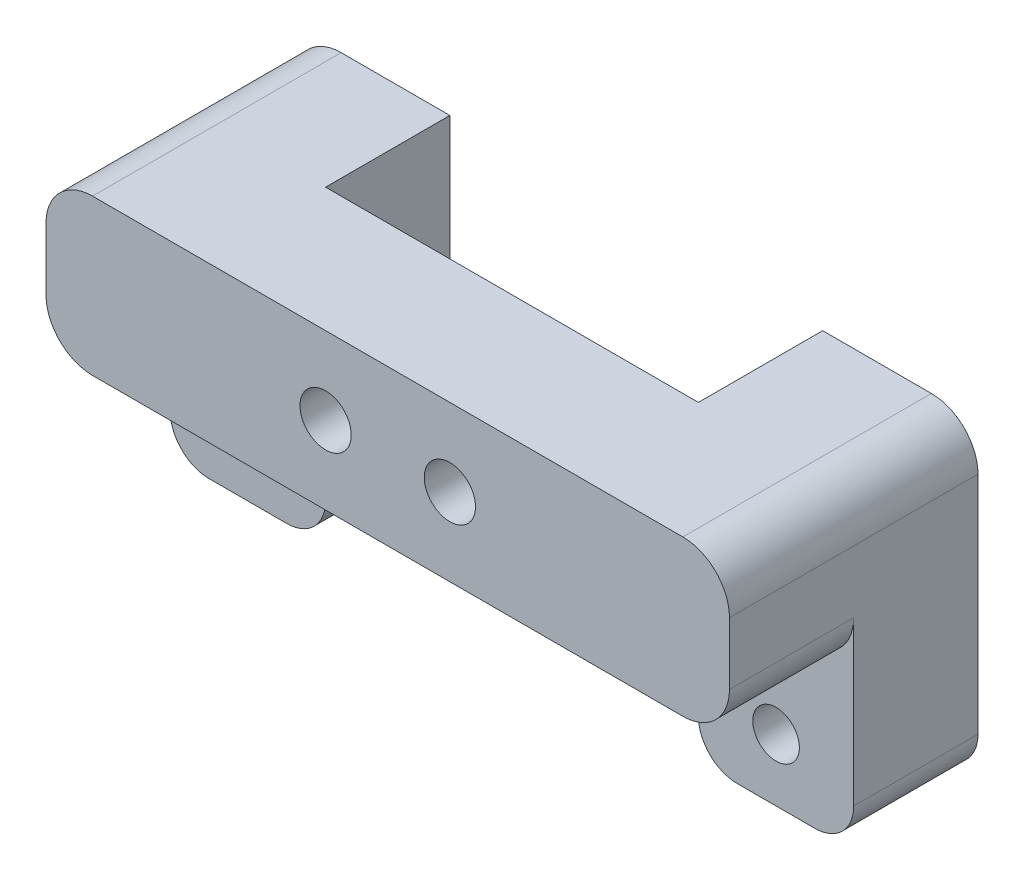
SolidWorks part; units mm, degrees
ref_plane "Front" through (0, 0, 0) normal (0, 0, 1) x (1, 0, 0)
ref_plane "Top" through (0, 0, 0) normal (0, 1, 0) x (1, 0, 0)
ref_plane "Right" through (0, 0, 0) normal (1, 0, 0) x (0, 0, -1)
sketch "Sketch1" plane through (0, 0, 0) normal (0, 0, 1) x (1, 0, 0)
  line L1 (0, 0) -> (44, 0)
  line L2 (0, 0) -> (0, -10)
  line L3 (0, -10) -> (44, -10)
  line L4 (44, 0) -> (44, -10)
  dimension "D1" = 10
  dimension "D2" = 44
extrude "Boss-Extrude1" add sketch "Sketch1" along normal blind 8
sketch "Sketch4" plane through (0, 0, 0) normal (0, 0, -1) x (-1, 0, 0)
  line L0 (-44, 0) -> (0, 0) construction
  line L1 (0, -10) -> (-10, -10)
  line L2 (0, -10) -> (0, 0)
  line L3 (0, 0) -> (-10, 0)
  line L4 (-10, -10) -> (-10, 0)
  line L6 (-44, -10) -> (-34, -10)
  line L7 (-44, -10) -> (-44, 0)
  line L8 (-44, 0) -> (-34, 0)
  line L9 (-34, -10) -> (-34, 0)
  dimension "D1" = 10
  dimension "D2" = 10
extrude "Boss-Extrude2" add sketch "Sketch4" along normal blind 8
sketch "Sketch3" plane through (0, 0, 8) normal (0, 0, 1) x (1, 0, 0)
  line L0 (0, -10) -> (44, -10) construction
  line L1 (0, 0) -> (0, -10) construction
  line L2 (44, -10) -> (44, 0) construction
  circle A0 centre (18, -5) radius 1.65
  circle A1 centre (26, -5) radius 1.65
  dimension "D1" = 3.3
  dimension "D2" = 3.3
  dimension "D3" = 5
  dimension "D4" = 5
  dimension "D5" = 18
  dimension "D6" = 18
extrude "Cut-Extrude2" cut sketch "Sketch3" against normal through all
sketch "Sketch5" plane through (0, -10, 0) normal (0, -1, 0) x (-1, 0, 0)
  line L1 (-10, 0) -> (0, 0)
  line L2 (-10, 0) -> (-10, 8)
  line L3 (-10, 8) -> (0, 8)
  line L4 (0, 0) -> (0, 8)
  line L5 (-34, 0) -> (-44, 0)
  line L6 (-34, 0) -> (-34, 8)
  line L7 (-34, 8) -> (-44, 8)
  line L8 (-44, 0) -> (-44, 8)
extrude "Boss-Extrude3" add sketch "Sketch5" along normal blind 10
sketch "Sketch6" plane through (0, 0, 0) normal (0, 0, 1) x (1, 0, 0)
  line L0 (10, -20) -> (0, -20) construction
  line L1 (44, -20) -> (34, -20) construction
  line L2 (44, -20) -> (44, -10) construction
  line L3 (10, -20) -> (10, -10) construction
  circle A0 centre (5, -16) radius 1.5
  circle A1 centre (39, -16) radius 1.5
  dimension "D1" = 3
  dimension "D2" = 3
  dimension "D3" = 4
  dimension "D4" = 4
  dimension "D5" = 5
  dimension "D6" = 5
extrude "Cut-Extrude3" cut sketch "Sketch6" against normal through all
fillet "Fillet2" radius 2.5 4 edges at (44, -20, -4) (34, -20, -4) (10, -20, -4) (0, -20, -4)
fillet "Fillet1" radius 3 4 edges at (0, -10, 4) (44, -10, 4) (44, 0, 0) (0, 0, 0)
equation "\"滑动-垂直孔\" = 0.6"
equation "\"滑动-水平孔\"= 0.3"
equation "\"松动-垂直孔\" = 0.3"
equation "\"松动-水平孔\"= 0.1"
equation "\"正常-垂直孔\" = 0.15"
equation "\"正常-水平孔\"= 0"
equation "\"紧缩-垂直孔\"= 0"
equation "\"紧缩-水平孔\"= - 0.1"
equation "\"D2@Sketch3\"=\"松动-垂直孔\"+3"
equation "\"D1@Sketch3\"=\"松动-垂直孔\"+3"
equation "\"D2@Sketch6\"=\"紧缩-垂直孔\"+3"
equation "\"D1@Sketch6\"=\"紧缩-垂直孔\"+3"
